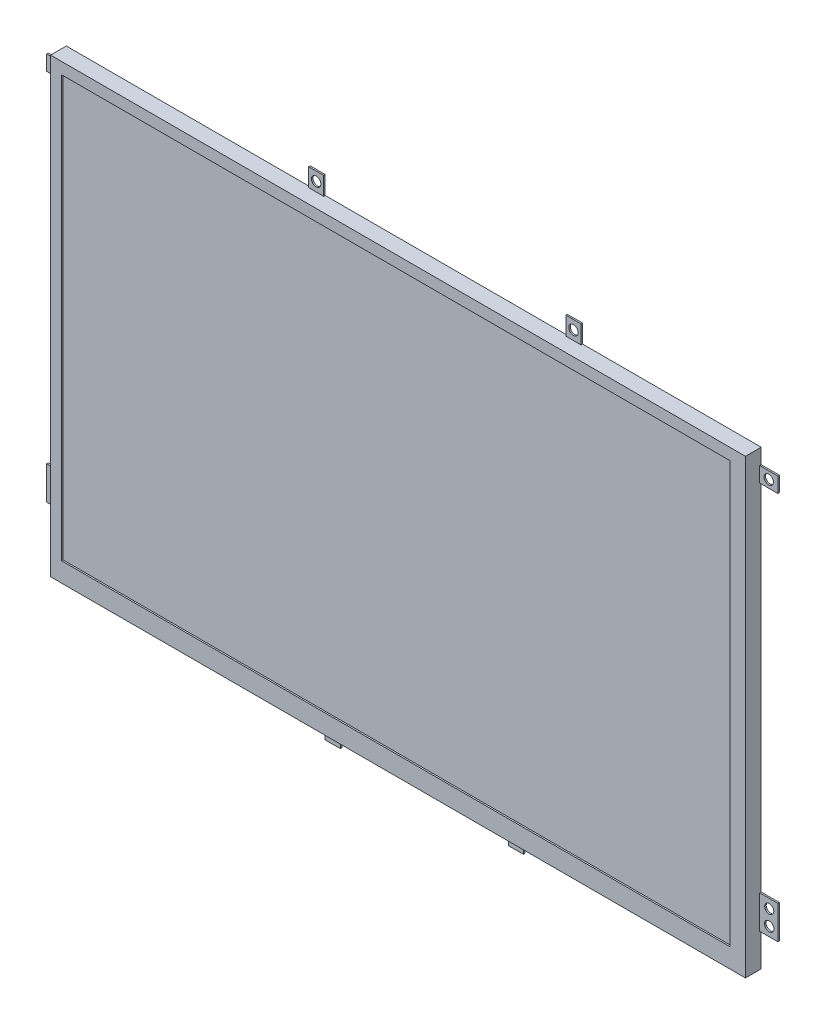
SolidWorks part; units mm, degrees
ref_plane "Front" through (0, 0, 0) normal (0, 0, 1) x (1, 0, 0)
ref_plane "Top" through (0, 0, 0) normal (0, 1, 0) x (1, 0, 0)
ref_plane "Right" through (0, 0, 0) normal (1, 0, 0) x (0, 0, -1)
sketch "Sketch1" plane through (0, 0, 0) normal (0, 0, 1) x (1, 0, 0)
  line L1 (0, 0) -> (229.46, 0)
  line L2 (0, 0) -> (0, 149.2)
  line L3 (0, 149.2) -> (229.46, 149.2)
  line L4 (229.46, 0) -> (229.46, 149.2)
  dimension "D1" = 229.46
  dimension "D2" = 149.2
extrude "Boss-Extrude1" add sketch "Sketch1" along normal blind 5.2
sketch "Sketch2" plane through (0, 0, 5.2) normal (0, 0, 1) x (1, 0, 0)
  line L1 (3.6, 145.4) -> (224.36, 145.4)
  line L2 (3.6, 145.4) -> (3.6, 6.4)
  line L3 (3.6, 6.4) -> (224.36, 6.4)
  line L4 (224.36, 145.4) -> (224.36, 6.4)
  line L5 (0, 149.2) -> (0, 0) construction
  line L7 (229.46, 149.2) -> (0, 149.2) construction
  dimension "D1" = 220.76
  dimension "D2" = 139
  dimension "D3" = 3.6
  dimension "D4" = 3.8
extrude "Cut-Extrude1" cut sketch "Sketch2" against normal blind 0.5
sketch "Sketch3" plane through (0, 0, 0) normal (0, 0, -1) x (-1, 0, 0)
  line L0 (-229.46, 0) -> (-229.46, 149.2) construction
  line L1 (-229.46, 144.2) -> (-235.46, 144.2)
  line L2 (-229.46, 144.2) -> (-229.46, 139.2)
  line L3 (-229.46, 139.2) -> (-235.46, 139.2)
  line L4 (-235.46, 144.2) -> (-235.46, 139.2)
  line L5 (-229.46, 149.2) -> (0, 149.2) construction
  line L6 (0, 0) -> (-229.46, 0) construction
  line L7 (-229.46, 22) -> (-235.46, 22)
  line L8 (-229.46, 22) -> (-229.46, 11)
  line L9 (-229.46, 11) -> (-235.46, 11)
  line L10 (-235.46, 22) -> (-235.46, 11)
  line L11 (0, 149.2) -> (0, 0) construction
  line L12 (-151.46, 0) -> (-146.46, 0)
  line L13 (-151.46, 0) -> (-151.46, -6)
  line L14 (-151.46, -6) -> (-146.46, -6)
  line L15 (-146.46, 0) -> (-146.46, -6)
  line L16 (-86, 0) -> (-91, 0)
  line L17 (-86, 0) -> (-86, -6)
  line L18 (-86, -6) -> (-91, -6)
  line L19 (-91, 0) -> (-91, -6)
  line L21 (0, 16) -> (6, 16)
  line L22 (0, 16) -> (0, 27)
  line L23 (0, 27) -> (6, 27)
  line L24 (6, 16) -> (6, 27)
  line L25 (0, 144.2) -> (6, 144.2)
  line L26 (0, 144.2) -> (0, 139.2)
  line L27 (0, 139.2) -> (6, 139.2)
  line L28 (6, 144.2) -> (6, 139.2)
  dimension "D1" = 5
  dimension "D2" = 6
  dimension "D3" = 5
  dimension "D4" = 11
  dimension "D5" = 11
  dimension "D6" = 5
  dimension "D7" = 6
  dimension "D8" = 78
  dimension "D9" = 6
  dimension "D10" = 5
  dimension "D11" = 86
  dimension "D12" = 11
  dimension "D13" = 6
  dimension "D14" = 16
  dimension "D15" = 6
  dimension "D16" = 5
  dimension "D17" = 5
extrude "Boss-Extrude2" add sketch "Sketch3" against normal blind 0.5
sketch "Sketch4" plane through (0, 0, 0) normal (0, 0, -1) x (-1, 0, 0)
  line L0 (-229.46, 149.2) -> (0, 149.2) construction
  line L1 (-170.46, 149.2) -> (-165.46, 149.2)
  line L2 (-170.46, 149.2) -> (-170.46, 155.2)
  line L3 (-170.46, 155.2) -> (-165.46, 155.2)
  line L4 (-165.46, 149.2) -> (-165.46, 155.2)
  line L5 (-229.46, 22) -> (-229.46, 139.2) construction
  line L6 (0, 139.2) -> (0, 27) construction
  line L7 (-80.5, 149.2) -> (-85.5, 149.2)
  line L8 (-80.5, 149.2) -> (-80.5, 155.2)
  line L9 (-80.5, 155.2) -> (-85.5, 155.2)
  line L10 (-85.5, 149.2) -> (-85.5, 155.2)
  dimension "D1" = 5
  dimension "D2" = 6
  dimension "D3" = 59
  dimension "D4" = 6
  dimension "D5" = 5
  dimension "D6" = 80.5
extrude "Boss-Extrude3" add sketch "Sketch4" against normal blind 0.5
hole_wizard "Ø3.1 (3.1) Diameter Hole1" positions "Sketch11" profile "Sketch12" hole size "Ø3.1" standard "ANSI Metric" end condition through all
sketch "Sketch11" plane through (0, 0, 0.5) normal (0, 0, 1) x (1, 0, 0)
  line L0 (-6, 144.2) -> (0, 144.2) construction
  line L1 (0, 149.2) -> (0, 0) construction
  line L2 (80.5, 149.2) -> (80.5, 155.2) construction
  line L3 (80.5, 155.2) -> (85.5, 155.2) construction
  line L4 (165.46, 155.2) -> (170.46, 155.2) construction
  line L5 (165.46, 149.2) -> (165.46, 155.2) construction
  line L6 (229.46, 144.2) -> (235.46, 144.2) construction
  line L7 (235.46, 144.2) -> (235.46, 139.2) construction
  line L8 (151.46, 0) -> (151.46, -6) construction
  line L9 (151.46, -6) -> (146.46, -6) construction
  line L10 (86, -6) -> (86, 0) construction
  line L11 (91, -6) -> (86, -6) construction
  point P0 (-3, 141.7)
  point P3 (83, 152.2)
  point P5 (167.96, 152.2)
  point P7 (232.46, 141.7)
  point P9 (148.96, -3)
  point P11 (88.5, -3)
  point P17 (-3, 144.2)
  point P24 (167.96, 155.2)
  dimension "D1" = 2.5
  dimension "D2" = 3
  dimension "D3" = 2.5
  dimension "D4" = 3
  dimension "D5" = 3
  dimension "D6" = 2.5
  dimension "D7" = 2.5
  dimension "D8" = 3
  dimension "D9" = 2.5
  dimension "D10" = 3
  dimension "D11" = 2.5
  dimension "D12" = 3
sketch "Sketch12" plane through (-3, 141.7, 0.5) normal (1, 0, 0) x (0, -1, 0)
  line L0 (0, 0) -> (0, 0.5001)
  line L1 (0, 0.5001) -> (1.55, 0.5001)
  line L2 (1.55, 0.5001) -> (1.55, 0)
  line L5 (1.55, 0) -> (0, 0)
  line L11 (0, -6.35) -> (0, 107.95) construction
  dimension "Thru Hole Dia." = 3.1
  dimension "Thru Hole Depth" = 0.5
hole_wizard "Ø3.1 (3.1) Diameter Hole4" positions "Sketch24" profile "Sketch25" hole size "Ø3.1" standard "ANSI Metric" end condition through all
sketch "Sketch24" plane through (0, 0, 0.5) normal (0, 0, 1) x (1, 0, 0)
  point P0 (232.6186, 14)
sketch "Sketch25" plane through (232.6186, 14, 0.5) normal (1, 0, 0) x (0, -1, 0)
  line L0 (0, 0) -> (0, 0.5001)
  line L1 (0, 0.5001) -> (1.55, 0.5001)
  line L2 (1.55, 0.5001) -> (1.55, 0)
  line L5 (1.55, 0) -> (0, 0)
  line L11 (0, -6.35) -> (0, 107.95) construction
  dimension "Thru Hole Dia." = 3.1
  dimension "Thru Hole Depth" = 0.5
hole_wizard "Ø2.5 (2.5) Diameter Hole2" positions "Sketch31" profile "Sketch32" hole size "Ø2.5" standard "ANSI Metric" end condition through all
sketch "Sketch31" plane through (0, 0, 0.5) normal (0, 0, 1) x (1, 0, 0)
  point P0 (-3, 24)
  point P3 (-2.9329, 19)
sketch "Sketch32" plane through (-3, 24, 0.5) normal (1, 0, 0) x (0, -1, 0)
  line L0 (0, 0) -> (0, 0.5)
  line L1 (0, 0.5) -> (1.25, 0.5)
  line L2 (1.25, 0.5) -> (1.25, 0)
  line L5 (1.25, 0) -> (0, 0)
  line L11 (0, -6.35) -> (0, 107.95) construction
  dimension "Thru Hole Dia." = 2.5
  dimension "Thru Hole Depth" = 0.5
hole_wizard "Ø3.0 (3) Diameter Hole1" positions "Sketch34" profile "Sketch35" hole size "Ø3.0" standard "ANSI Metric" end condition through all
sketch "Sketch34" plane through (0, 0, 0.5) normal (0, 0, 1) x (1, 0, 0)
  point P0 (232.6186, 19)
sketch "Sketch35" plane through (232.6186, 19, 0.5) normal (1, 0, 0) x (0, -1, 0)
  line L0 (0, 0) -> (0, 0.5001)
  line L1 (0, 0.5001) -> (1.5, 0.5001)
  line L2 (1.5, 0.5001) -> (1.5, 0)
  line L5 (1.5, 0) -> (0, 0)
  line L11 (0, -6.35) -> (0, 107.95) construction
  dimension "Thru Hole Dia." = 3
  dimension "Thru Hole Depth" = 0.5
